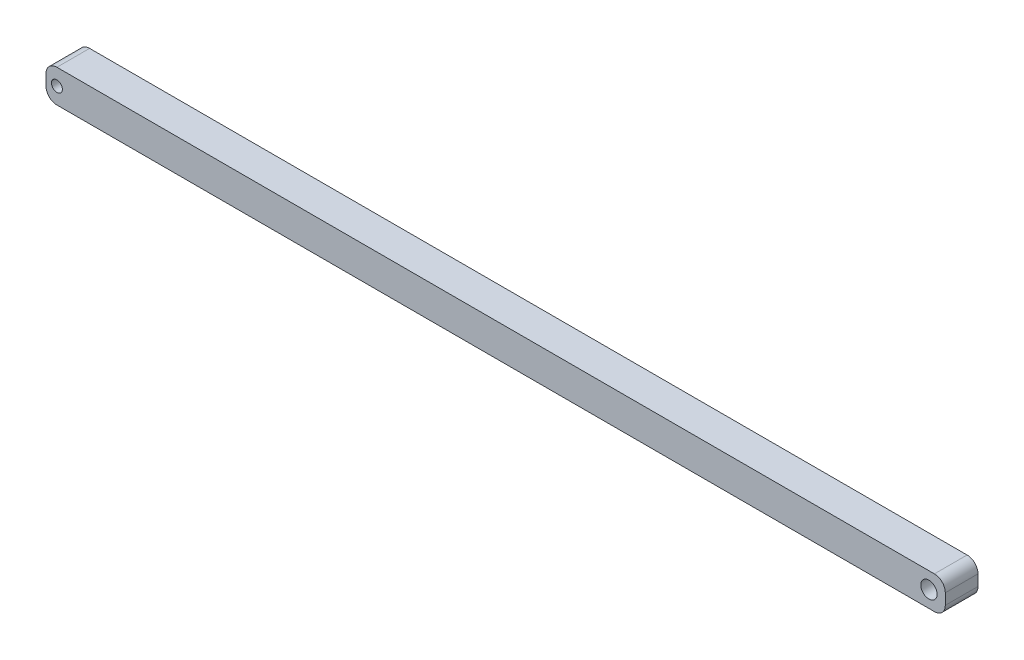
SolidWorks part; units mm, degrees
ref_plane "Plan de face" through (0, 0, 0) normal (0, 0, 1) x (1, 0, 0)
ref_plane "Plan de dessus" through (0, 0, 0) normal (0, 1, 0) x (1, 0, 0)
ref_plane "Plan de droite" through (0, 0, 0) normal (1, 0, 0) x (0, 0, -1)
sketch "Esquisse1" plane through (0, 0, 0) normal (0, 0, 1) x (1, 0, 0)
  line L1 (0, 0) -> (165, 0)
  line L2 (0, 0) -> (0, 6)
  line L3 (0, 6) -> (165, 6)
  line L4 (165, 0) -> (165, 6)
extrude "Boss.-Extru.1" add sketch "Esquisse1" along normal blind 6
sketch "Esquisse2" plane through (0, 0, 6) normal (0, 0, 1) x (1, 0, 0)
  line L0 (0, 3) -> (165, 3) construction
  line L1 (0, 6) -> (0, 0) construction
  line L2 (165, 0) -> (165, 6) construction
  circle A0 centre (162, 3) radius 1.5
  circle A1 centre (2, 3) radius 1
extrude "Enlèv. mat.-Extru.1" cut sketch "Esquisse2" against normal through all
fillet "Congé1" radius 2 4 edges at (0, 0, 3) (0, 6, 3) (165, 0, 3) (165, 6, 3)
